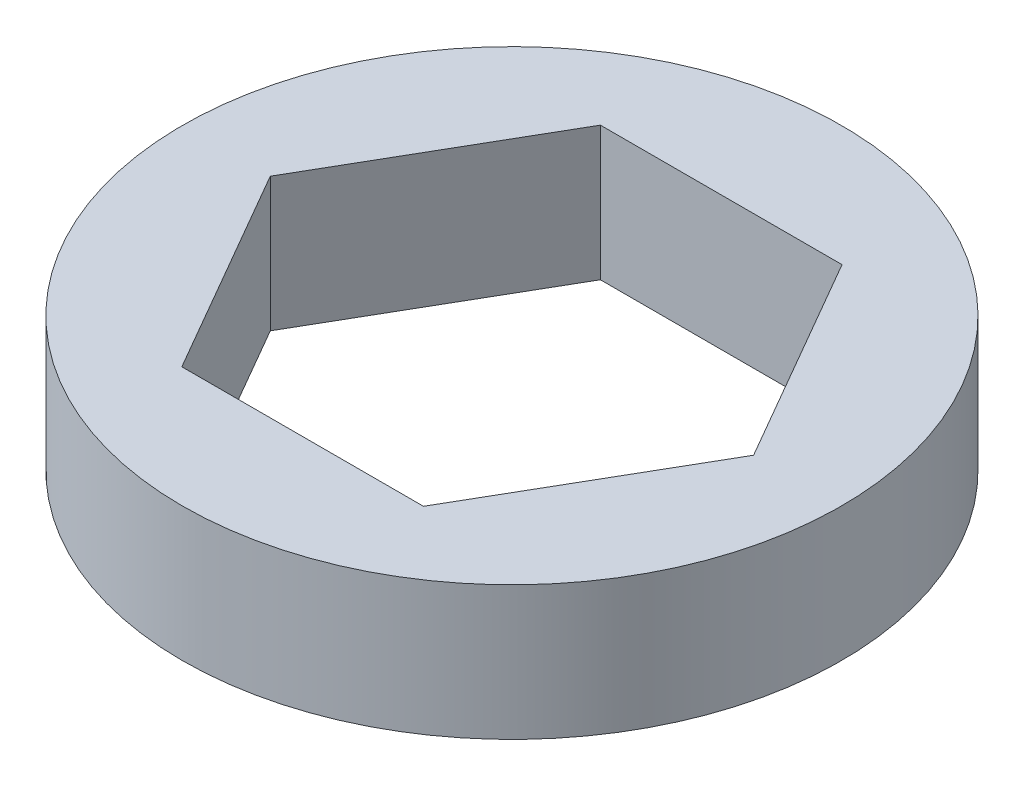
SolidWorks part; units mm, degrees
ref_plane "Front Plane" through (0, 0, 0) normal (0, 0, 1) x (1, 0, 0)
ref_plane "Top Plane" through (0, 0, 0) normal (0, 1, 0) x (1, 0, 0)
ref_plane "Right Plane" through (0, 0, 0) normal (1, 0, 0) x (0, 0, -1)
sketch "Sketch1" plane through (0, 0, 0) normal (0, 1, 0) x (1, 0, 0)
  line L1 (-7.3323, 0) -> (-3.6662, -6.35)
  line L2 (-3.6662, -6.35) -> (3.6662, -6.35)
  line L3 (3.6662, -6.35) -> (7.3323, 0)
  line L4 (7.3323, 0) -> (3.6662, 6.35)
  line L5 (3.6662, 6.35) -> (-3.6662, 6.35)
  line L6 (-3.6662, 6.35) -> (-7.3323, 0)
  circle A0 centre (0, 0) radius 10
  circle A1 centre (0, 0) radius 6.35 construction
  dimension "D2" = 20
  dimension "D1" = 12.7
extrude "Boss-Extrude1" add sketch "Sketch1" along normal blind 4.064
